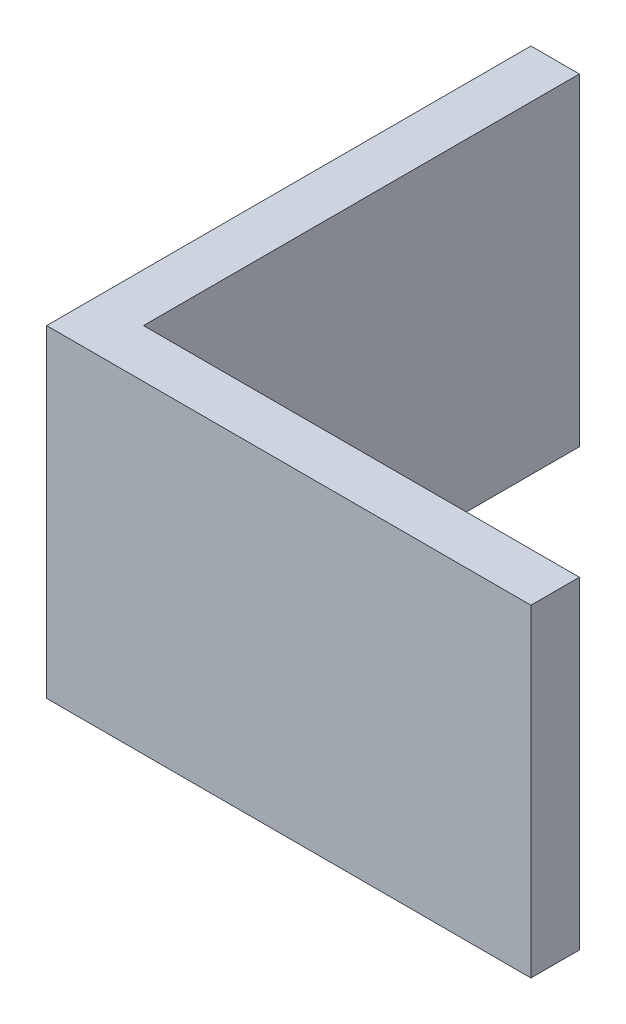
SolidWorks part; units mm, degrees
ref_plane "Front Plane" through (0, 0, 0) normal (0, 0, 1) x (1, 0, 0)
ref_plane "Top Plane" through (0, 0, 0) normal (0, 1, 0) x (1, 0, 0)
ref_plane "Right Plane" through (0, 0, 0) normal (1, 0, 0) x (0, 0, -1)
sketch "Sketch2" plane through (0, 0, 0) normal (0, 1, 0) x (1, 0, 0)
  line L0 (0, 0) -> (0, -30)
  line L1 (0, -30) -> (30, -30)
  line L2 (30, -30) -> (30, -27)
  line L3 (0, 0) -> (3, 0)
  line L4 (3, 0) -> (3, -27)
  line L5 (3, -27) -> (30, -27)
extrude "Boss-Extrude1" add sketch "Sketch2" along normal blind 20
